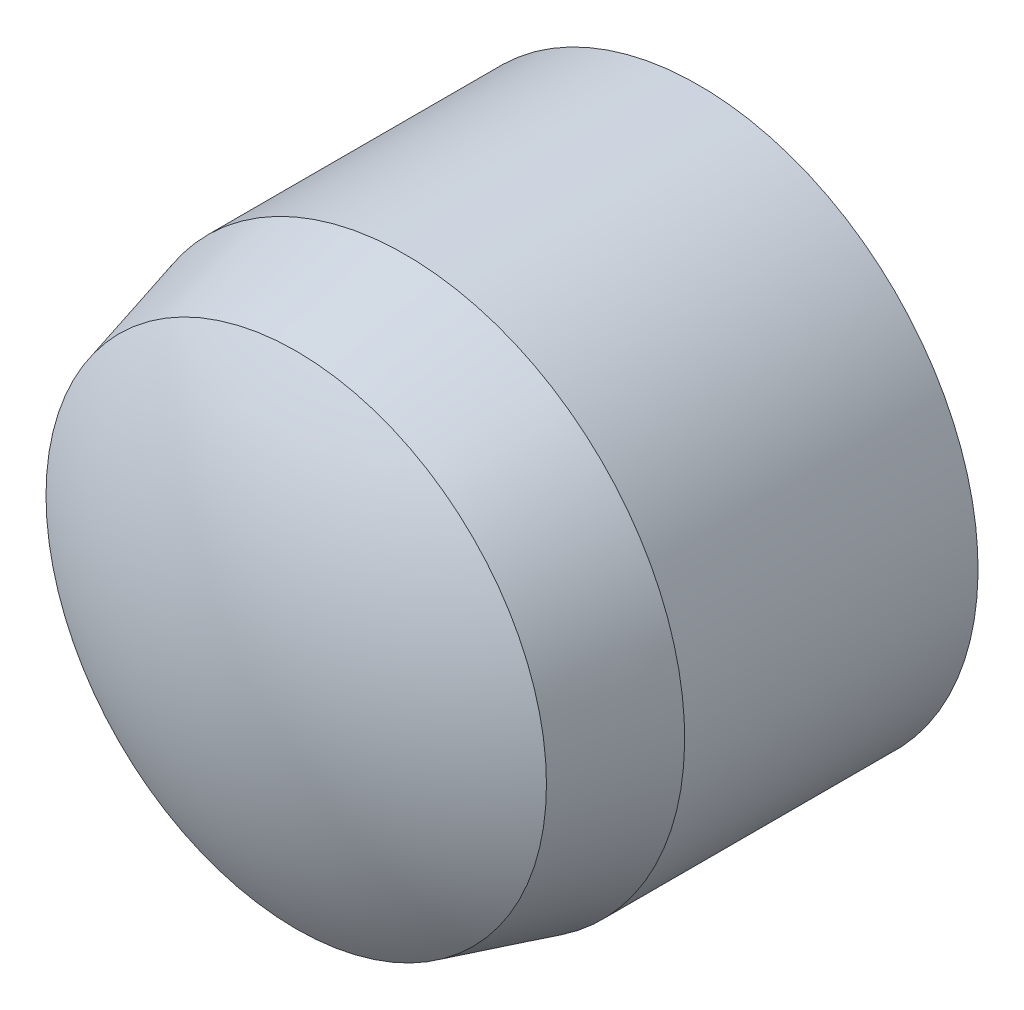
SolidWorks part; units mm, degrees
ref_plane "Front Plane" through (0, 0, 0) normal (0, 0, 1) x (1, 0, 0)
ref_plane "Top Plane" through (0, 0, 0) normal (0, 1, 0) x (1, 0, 0)
ref_plane "Right Plane" through (0, 0, 0) normal (1, 0, 0) x (0, 0, -1)
sketch "Sketch1" plane through (0, 0, 0) normal (0, 0, 1) x (1, 0, 0)
  circle A0 centre (0, 0) radius 2.5
  point P3 (0, 2.5)
  dimension "Diameter" = 5
sketch "Sketch2" plane through (0, 0, 0) normal (1, 0, 0) x (0, 0, -1)
  line L0 (-2.5, 0) -> (2.5, 0) construction
  line L1 (-2.5, 0) -> (-2.5, 2.5) construction
  line L2 (-2.5, 2.5) -> (2.5, 2.5)
  line L3 (2.5, 2.5) -> (2.5, 0) construction
  line L4 (-1.85, 2.2387) -> (-0.875, 2.5)
  arc A0 (-2.5, 0) -> (-1.85, 2.2387) centre (1.6804, 0) cw
  arc A1 (2.5, 0) -> (1.75, 2.5) centre (-2.0417, 0) ccw
  point P2 (0, 0)
  dimension "Length" = 5
  dimension "D1" = 15
  dimension "D2" = 0.75
  dimension "D3" = 1.625
  dimension "D4" = 0.975
sketch "Sketch3" plane through (0, 0, 0) normal (1, 0, 0) x (0, 0, -1)
  line L0 (-2.5, 0) -> (2.5, 0) construction
  line L1 (-1.85, 2.2387) -> (-0.875, 2.5) construction
  line L2 (-2.5, 0) -> (2.5, 0)
  line L3 (-1.85, 2.2387) -> (-0.875, 2.5)
  line L4 (-0.875, 2.5) -> (1.75, 2.5)
  arc A0 (2.5, 0) -> (1.75, 2.5) centre (-2.0417, 0) ccw construction
  arc A1 (-1.85, 2.2387) -> (-2.5, 0) centre (1.6804, 0) ccw construction
  arc A2 (2.5, 0) -> (1.75, 2.5) centre (-2.0417, 0) ccw
  arc A3 (-1.85, 2.2387) -> (-2.5, 0) centre (1.6804, 0) ccw
revolve "Revolve1" add sketch "Sketch3" angle 360 about L2
equation "\"D2@Sketch2\" = \"Diameter@Sketch1\" * .15"
equation "\"D3@Sketch2\" = \"Diameter@Sketch1\" * .325"
equation "\"D4@Sketch2\" = \"D3@Sketch2\" * .6"
